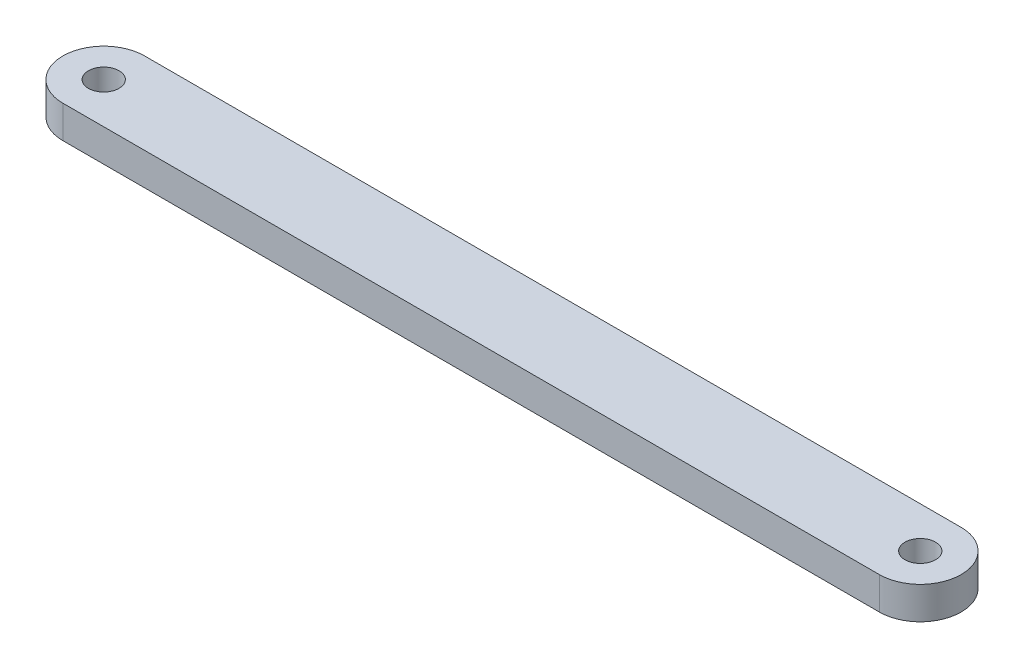
SolidWorks part; units mm, degrees
material "Acrylic (Medium-high impact)"
ref_plane "Front Plane" through (0, 0, 0) normal (0, 0, 1) x (1, 0, 0)
ref_plane "Top Plane" through (0, 0, 0) normal (0, 1, 0) x (1, 0, 0)
ref_plane "Right Plane" through (0, 0, 0) normal (1, 0, 0) x (0, 0, -1)
sketch "Sketch1" plane through (0, 0, 0) normal (0, 1, 0) x (1, 0, 0)
  line L0 (40.0183, 4.0001) -> (-39.84, 4.0001)
  line L1 (-39.84, -4.0001) -> (40.0183, -4.0001)
  arc A0 (-39.84, 4.0001) -> (-39.84, -4.0001) centre (-39.84, 0) ccw
  arc A1 (40.0183, -4.0001) -> (40.0183, 4.0001) centre (40.0183, 0) ccw
  circle A2 centre (-39.84, 0) radius 1.4973
  circle A3 centre (40.0183, 0) radius 1.4973
  dimension "D1" = 2.9946
extrude "Boss-Extrude1" add sketch "Sketch1" along normal blind 3.175
